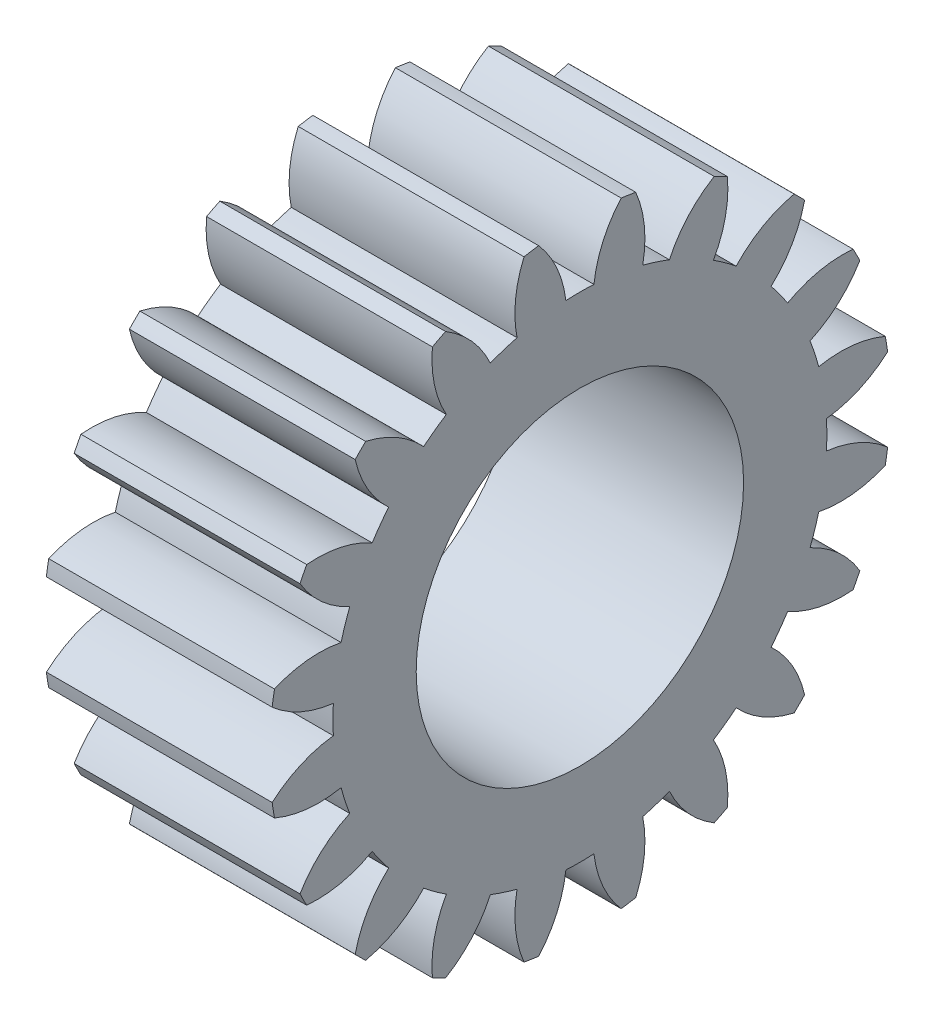
SolidWorks part; units mm, degrees
ref_plane "Plane1" through (0, 0, 0) normal (0, 0, 1) x (1, 0, 0)
ref_plane "Plane2" through (0, 0, 0) normal (0, 1, 0) x (1, 0, 0)
ref_plane "Plane3" through (0, 0, 0) normal (1, 0, 0) x (0, 0, -1)
sketch "HoldingSke" plane through (0, 0, 0) normal (0, 1, 0) x (1, 0, 0)
  line L0 (0, 0) -> (0.7518, -0.2736)
  line L1 (-15, 0) -> (100, 0) construction
  line L2 (0, 0) -> (-2.1039, 2.3779)
  line L3 (0, 0) -> (-11.863, 4.5341)
  line L4 (0, 0) -> (8.1152, 2.9537)
  line L5 (0, 0) -> (-46.8476, -17.4728)
  line L6 (0, 0) -> (-8.2896, -5.593)
  line L7 (-2.1039, 2.3779) -> (8.6586, 51.2059)
  line L8 (-76.2, 54.61) -> (-73.9, 54.61)
  line L9 (-71.009, 38.7566) -> (-53.1078, 45.2721)
  line L10 (-76.2, 71.12) -> (104.1128, 71.12)
  line L11 (0, 0) -> (-10, 0)
  line L12 (-76.2, 101.6) -> (-76.155, 101.6)
  line L13 (24.9733, 27.94) -> (52.9518, 28.4284)
  line L14 (24.9733, 27.94) -> (24.9743, 27.94)
  line L15 (24.9733, 27.94) -> (100.4006, 29.5858)
  line L16 (-63.627, -1.25) -> (-12.827, -1.25)
  circle A0 centre (0, 0) radius 7
  circle A1 centre (0, 0) radius 10.9365
  circle A2 centre (0, 0) radius 37.5
  circle A3 centre (0, 0) radius 7
  dimension "MHD" = 21.873
  dimension "Hub_dia" = 75
  dimension "Bore" = 14
  dimension "MBD" = 14
  dimension "Num_teeth" = 20
  dimension "Pitch" = 0.8
  dimension "Overall_len" = 50
  dimension "Show_teeth" = 20
  dimension "Thickness" = 10
  dimension "OAL" = 50.0001
  dimension "T_dim" = 2.3
  dimension "Ap" = 20
  dimension "H" = 19.05
  dimension "Pitch_radius" = 180.3128
  dimension "Width" = 10
  dimension "Backlash" = 0.045
  dimension "Addendum_fac" = 1
  dimension "Dedendum_fac" = 1.25
  dimension "Clearance_fac" = 0.25
  dimension "Dedendum_add" = 0.001
  dimension "Module" = 1.25
sketch "BasProSke" plane through (0, 0, 0) normal (0, 1, 0) x (1, 0, 0)
  line L0 (-10, 0) -> (60, 0) construction
  line L1 (0, 0) -> (0, 13.75)
  line L2 (0, 0) -> (10, 0)
  line L3 (10, 0) -> (10, 13.75)
  line L4 (10, 13.75) -> (0, 13.75)
  dimension "Thickness" = 10
  dimension "Diameter" = 27.5
revolve "Base-Revolve" add sketch "BasProSke" angle 360 about L0
sketch "TooCutSke" plane through (0, 0, 0) normal (1, 0, 0) x (0, 0, -1)
  line L1 (0, 0) -> (0, 107) construction
  line L2 (0, 0) -> (-1.0594, 12.455) construction
  line L3 (0, 0) -> (-3.9007, 24.6278) construction
  line L4 (-1.0594, 12.455) -> (-1.9503, 12.3139) construction
  arc A0 (0.6211, 10.9188) -> (-0.6211, 10.9188) centre (0, 0) ccw
  arc A1 (1.8466, 13.6511) -> (-1.8466, 13.6511) centre (0, 0) ccw
  circle A2 centre (0, 0) radius 12.5 construction
  circle A3 centre (0, 0) radius 11.7462 construction
  arc A4 (-0.6211, 10.9188) -> (-1.8466, 13.6511) centre (-5.5866, 10.3326) ccw
  arc A5 (1.8466, 13.6511) -> (0.6211, 10.9188) centre (5.5866, 10.3326) ccw
  dimension "Root_dia" = 21.873
  dimension "Overcut_dia" = 27.5508
  dimension "Pitch_dia" = 25
  dimension "Base_dia" = 23.4923
  dimension "Flank_rad" = 5
  dimension "Half_ang" = 9
  dimension "Half_CT" = 0.902
extrude "ToothCut" cut sketch "TooCutSke" along normal through all
fillet "Breaks" [suppressed] radius 0.025
fillet "RootFillets" [suppressed] radius 0.3135
pattern_circular "TeethCuts" count 20 every 18 about axis through (-10, 0, 0) along (1, 0, 0) of "ToothCut", "RootFillets", "Breaks"
sketch "HubNeaOneSke" plane through (0, 0, 0) normal (-1, 0, 0) x (0, 0, 1)
  circle A0 centre (0, 0) radius 10.9365
  dimension "Diameter" = 21.873
extrude "HubNearOne" [suppressed] add sketch "HubNeaOneSke" along normal blind 40.0001
sketch "HubNeaBotSke" plane through (0, 0, 0) normal (-1, 0, 0) x (0, 0, 1)
  circle A0 centre (0, 0) radius 10.9365
  dimension "Diameter" = 21.873
extrude "HubNearBoth" [suppressed] add sketch "HubNeaBotSke" along normal blind 20
ref_plane "FarPln" through (10, 0, 0) normal (1, 0, 0) x (0, 0, -1)
sketch "HubFarSke" plane through (10, 0, 0) normal (1, 0, 0) x (0, 0, -1)
  circle A0 centre (0, 0) radius 10.9365
  dimension "Diameter" = 21.873
extrude "HubFar" [suppressed] add sketch "HubFarSke" along normal blind 20
sketch "BorSke" plane through (0, 0, 0) normal (1, 0, 0) x (0, 0, -1)
  circle A0 centre (0, 0) radius 7
  dimension "Diameter" = 14
extrude "Bore" cut sketch "BorSke" along normal mid plane 100.0001
sketch "KeySke" plane through (0, 0, 0) normal (1, 0, 0) x (0, 0, -1)
  line L0 (-2.5, 0) -> (-2.5, 9.3)
  line L1 (-2.5, 9.3) -> (2.5, 9.3)
  line L2 (2.5, 9.3) -> (2.5, 0)
  line L3 (0, 0) -> (0, 34) construction
  line L4 (-2.5, 0) -> (2.5, 0)
  dimension "Offset" = 9.3
  dimension "Width" = 5
extrude "Keyway" [suppressed] cut sketch "KeySke" along normal mid plane 100.0001
pattern_circular "Keyway2" [suppressed] count 2 every 90 about axis through (-10, 0, 0) along (1, 0, 0)
sketch "Sketch1" plane through (10, 0, 0) normal (1, 0, 0) x (0, 0, -1)
sketch "Sketch2" plane through (10, 0, 0) normal (1, 0, 0) x (0, 0, -1)
  circle A0 centre (0, 0) radius 7.25
  dimension "D1" = 14.5
extrude "Cut-Extrude1" cut sketch "Sketch2" against normal blind 10
equation "' \"Module@HoldingSke\" = 6.35"
equation "' \"Num_teeth@HoldingSke\" = 12"
equation "' \"Ap@HoldingSke\" =  20"
equation "' \"Ap@HoldingSke\" = 20"
equation "' \"Width@HoldingSke\" = 0.5 * 25.4"
equation "' \"Hub_dia@HoldingSke\"= 1 * 25.4"
equation "' \"Hub_dia@HoldingSke\" = 1 * 25.4"
equation "' \"Overall_len@HoldingSke\" = 1.0 * 25.4"
equation "' \"Bore@HoldingSke\" = 0.75 * 25.4"
equation "' \"T_dim@HoldingSke\" = 0.1 * 25.4"
equation "' \"Width@KeySke\" = 0.25 * 25.4"
equation "' \"Show_teeth@HoldingSke\" = 13"
equation "' \"Backlash@HoldingSke\" = 0.009 * 25.4"
equation "' \"Addendum_fac@HoldingSke\" = 1.0"
equation "' \"Dedendum_fac@HoldingSke\" = 1.25"
equation "' \"Dedendum_add@HoldingSke\" = 0.00005 * 25.4"
equation "' \"Clearance_fac@HoldingSke\" = 0.25"
equation "\"Pitch@HoldingSke\" = 1 / \"Module@HoldingSke\""
equation "\"Overcut_dia@TooCutSke\" = (\"Num_teeth@HoldingSke\" + 2 * \"Addendum_fac@HoldingSke\") / \"Pitch@HoldingSke\" + 0.002 * 25.4"
equation "\"Pitch_dia@TooCutSke\" = \"Num_teeth@HoldingSke\" / \"Pitch@HoldingSke\""
equation "\"Base_dia@TooCutSke\" = \"Num_teeth@HoldingSke\" / \"Pitch@HoldingSke\" * cos((\"Ap@HoldingSke\"  * 3.14159265 / 180))"
equation "\"Root_dia@TooCutSke\" = (\"Num_teeth@HoldingSke\" + 2) / \"Pitch@HoldingSke\" - 2 * (\"Addendum_fac@HoldingSke\" + \"Dedendum_fac@HoldingSke\") / \"Pitch@HoldingSke\" - \"Dedendum_add@HoldingSke\" * 2"
equation "\"Half_ang@TooCutSke\" = 180 / \"Num_teeth@HoldingSke\""
equation "\"Half_CT@TooCutSke\" = \"Num_teeth@HoldingSke\" / \"Pitch@HoldingSke\" * sin((3.14159265 / 2 / \"Num_teeth@HoldingSke\")) / 2 - 7 * \"Backlash@HoldingSke\" / 4"
equation "\"Flank_rad@TooCutSke\" = \"Num_teeth@HoldingSke\" / \"Pitch@HoldingSke\" / 5"
equation "\"Radius@RootFillets\" = \"Clearance_fac@HoldingSke\" / \"Pitch@HoldingSke\" + \"Dedendum_add@HoldingSke\""
equation "\"Break_rad@Breaks\" = 0.02 / \"Pitch@HoldingSke\""
equation "\"Thickness@HoldingSke\" = \"Width@HoldingSke\""
equation "\"OAL@HoldingSke\" = \"Thickness@HoldingSke\""
equation "\"MHD@HoldingSke\" = (\"Num_teeth@HoldingSke\" + 2) / \"Pitch@HoldingSke\" - 2 * (\"Addendum_fac@HoldingSke\" + \"Dedendum_fac@HoldingSke\")  / \"Pitch@HoldingSke\" - \"Dedendum_add@HoldingSke\" * 2"
equation "\"MBD@HoldingSke\" = (\"Num_teeth@HoldingSke\" + 2) / \"Pitch@HoldingSke\" - 2 * (\"Addendum_fac@HoldingSke\" + \"Dedendum_fac@HoldingSke\")  / \"Pitch@HoldingSke\" - \"Dedendum_add@HoldingSke\" * 2 - 0.002 * 25.4"
equation "\"MHD@HoldingSke\" = ((sgn( \"MHD@HoldingSke\" - \"Hub_dia@HoldingSke\" )-1)*( \"MHD@HoldingSke\" - \"Hub_dia@HoldingSke\" ))/-2+ \"Hub_dia@HoldingSke\""
equation "\"MBD@HoldingSke\" = ((sgn( \"MBD@HoldingSke\" - \"Bore@HoldingSke\" )-1)*( \"MBD@HoldingSke\" - \"Bore@HoldingSke\" ))/-2+ \"Bore@HoldingSke\""
equation "\"OAL@HoldingSke\" = ((sgn( \"OAL@HoldingSke\" - \"Overall_len@HoldingSke\" )+1)*( \"OAL@HoldingSke\" - \"Overall_len@HoldingSke\" ))/2 + \"Overall_len@HoldingSke\" + 0.000002 * 25.4"
equation "\"Num_teeth@TeethCuts\" = int( \"Show_teeth@HoldingSke\" ) + 1"
equation "\"Num_teeth@TeethCuts\" = ((sgn( \"Num_teeth@TeethCuts\" - \"Num_teeth@HoldingSke\" )-1)*( \"Num_teeth@TeethCuts\" - \"Num_teeth@HoldingSke\" ))/-2+ \"Num_teeth@HoldingSke\""
equation "\"Num_teeth@TeethCuts\" = ((sgn( \"Num_teeth@TeethCuts\" - 2.0)+1)*( \"Num_teeth@TeethCuts\" - 2.0))/2 +2.0"
equation "\"Angle@TeethCuts\" = 360.0 / \"Num_teeth@HoldingSke\""
equation "\"Diameter@BasProSke\" = (\"Num_teeth@HoldingSke\" + 2 * \"Addendum_fac@HoldingSke\") / \"Pitch@HoldingSke\""
equation "\"Thickness@BasProSke\"  = \"Thickness@HoldingSke\""
equation "' \"Fillet_rad@BasProSke\" =  \"Thickness@HoldingSke\" * 0.05"
equation "' \"Fillet_rad@BasProSke\" = \"Thickness@HoldingSke\" * 0.05"
equation "\"MHD@HoldingSke\" = ((sgn( \"MHD@HoldingSke\" - \"Root_dia@TooCutSke\" )-1)*( \"MHD@HoldingSke\" - \"Root_dia@TooCutSke\" ))/-2+ \"Root_dia@TooCutSke\""
equation "\"Diameter@HubNeaOneSke\" = \"MHD@HoldingSke\""
equation "\"Length@HubNearOne\" = \"OAL@HoldingSke\" - \"Thickness@BasProSke\""
equation "\"Diameter@HubNeaBotSke\" = \"MHD@HoldingSke\""
equation "\"Length@HubNearBoth\" = ( \"OAL@HoldingSke\" - \"Thickness@BasProSke\" ) / 2.0"
equation "\"Thickness@FarPln\" = \"Thickness@BasProSke\""
equation "\"Diameter@HubFarSke\" = \"MHD@HoldingSke\""
equation "\"Length@HubFar\" = ( \"OAL@HoldingSke\" - \"Thickness@BasProSke\" ) / 2.0"
equation "\"Diameter@BorSke\" = \"MBD@HoldingSke\""
equation "\"D1@Bore\" = \"OAL@HoldingSke\" * 2.0"
equation "\"D1@Keyway\" = \"OAL@HoldingSke\" * 2.0"
equation "\"Offset@KeySke\" = \"T_dim@HoldingSke\" + \"MBD@HoldingSke\" / 2.0"
